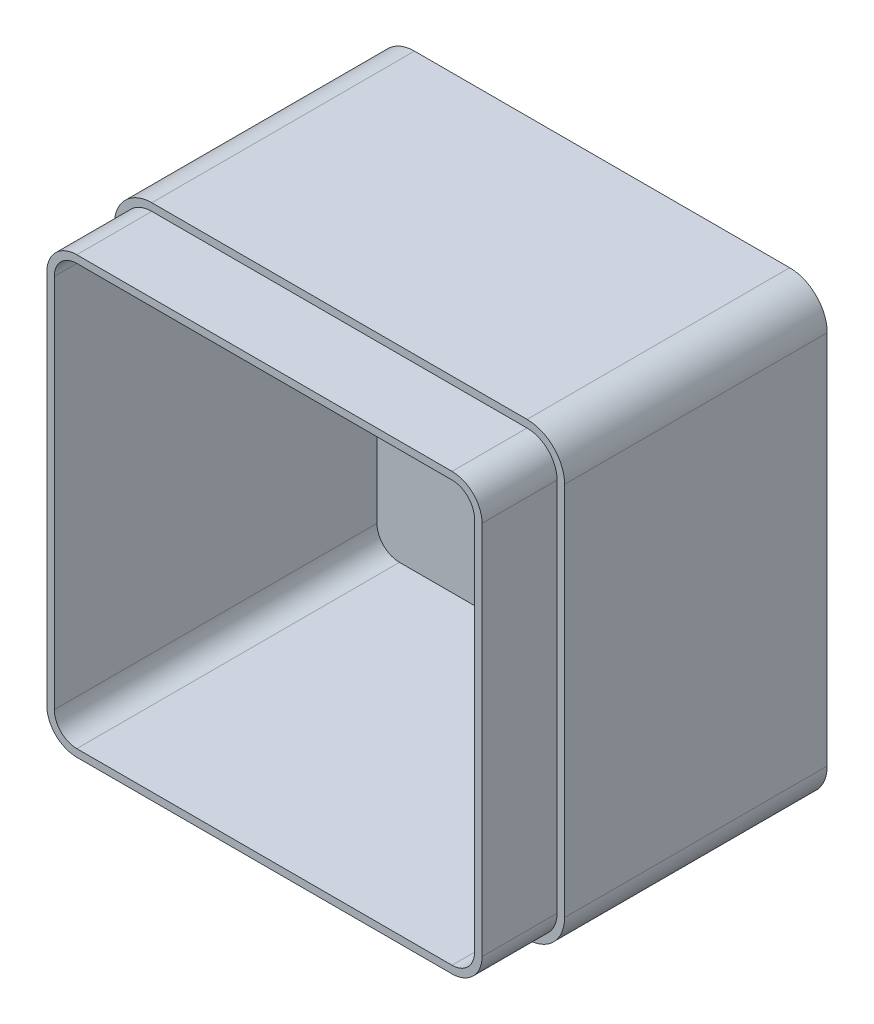
SolidWorks part; units mm, degrees
material "Chêne"
ref_plane "Plan de face" through (0, 0, 0) normal (0, 0, 1) x (1, 0, 0)
ref_plane "Plan de dessus" through (0, 0, 0) normal (0, 1, 0) x (1, 0, 0)
ref_plane "Plan de droite" through (0, 0, 0) normal (1, 0, 0) x (0, 0, -1)
sketch "Esquisse1" plane through (0, 0, 0) normal (0, 0, 1) x (1, 0, 0)
  line L1 (0, 0) -> (-120, 0)
  line L2 (0, 0) -> (0, -120)
  line L3 (0, -120) -> (-120, -120)
  line L4 (-120, 0) -> (-120, -120)
  dimension "D1" = 120
  dimension "D2" = 120
extrude "Boss.-Extru.1" add sketch "Esquisse1" along normal blind 90
fillet "Congé1" radius 10 4 edges at (-120, -120, 45) (0, -120, 45) (0, 0, 45) (-120, 0, 45)
shell "Coque2" thickness 4
sketch "Esquisse5" plane through (0, 0, 90) normal (0, 0, 1) x (1, 0, 0)
  line L0 (-118, -10) -> (-118, -110)
  line L1 (-110, -118) -> (-10, -118)
  line L2 (-2, -110) -> (-2, -10)
  line L3 (-10, -2) -> (-110, -2)
  line L4 (-120, -10) -> (-120, -110)
  line L5 (-110, -120) -> (-10, -120)
  line L6 (0, -110) -> (0, -10)
  line L7 (-10, 0) -> (-110, 0)
  line L8 (-120, -10) -> (-120, -110)
  line L9 (-110, -120) -> (-10, -120)
  line L10 (0, -110) -> (0, -10)
  line L11 (-10, 0) -> (-110, 0)
  arc A0 (-118, -110) -> (-110, -118) centre (-110, -110) ccw
  arc A1 (-10, -118) -> (-2, -110) centre (-10, -110) ccw
  arc A2 (-2, -10) -> (-10, -2) centre (-10, -10) ccw
  arc A3 (-110, -2) -> (-118, -10) centre (-110, -10) ccw
  arc A4 (-120, -110) -> (-110, -120) centre (-110, -110) ccw
  arc A5 (-10, -120) -> (0, -110) centre (-10, -110) ccw
  arc A6 (0, -10) -> (-10, 0) centre (-10, -10) ccw
  arc A7 (-110, 0) -> (-120, -10) centre (-110, -10) ccw
  arc A8 (-120, -110) -> (-110, -120) centre (-110, -110) ccw
  arc A9 (-10, -120) -> (0, -110) centre (-10, -110) ccw
  arc A10 (0, -10) -> (-10, 0) centre (-10, -10) ccw
  arc A11 (-110, 0) -> (-120, -10) centre (-110, -10) ccw
  dimension "D1" = 0
  dimension "D2" = 2
extrude "Enlèv. mat.-Extru.2" cut sketch "Esquisse5" against normal blind 20
